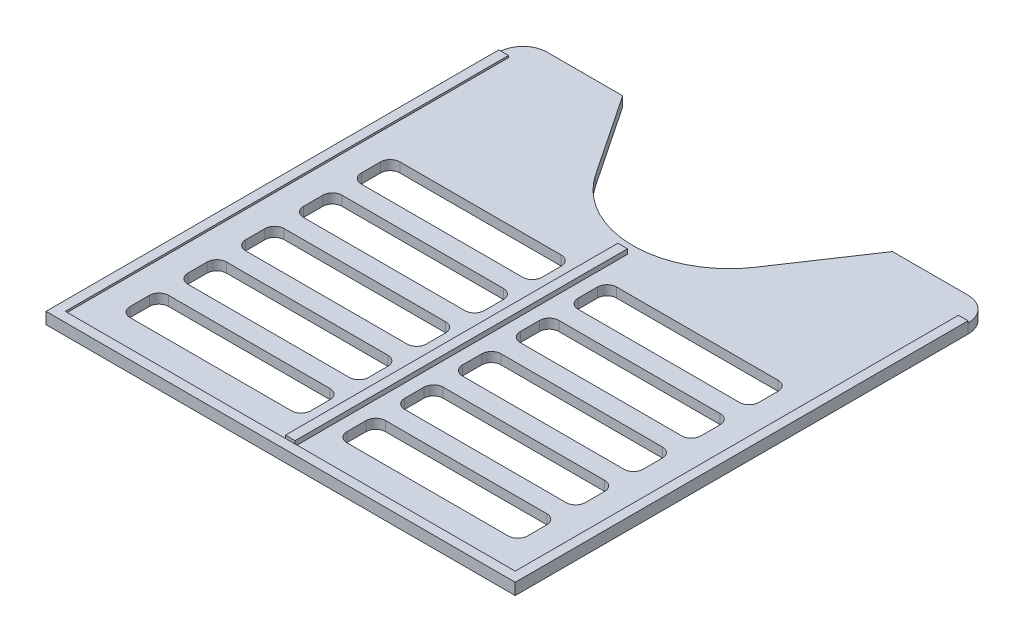
SolidWorks part; units mm, degrees
material "PVC hart"
ref_plane "Ebene vorne" through (0, 0, 0) normal (0, 0, 1) x (1, 0, 0)
ref_plane "Ebene oben" through (0, 0, 0) normal (0, 1, 0) x (1, 0, 0)
ref_plane "Ebene rechts" through (0, 0, 0) normal (1, 0, 0) x (0, 0, -1)
sketch "Skizze2" plane through (0, 0, 0) normal (0, 1, 0) x (1, 0, 0)
  line L0 (0, 82.3632) -> (0, -81.2206) construction
  line L6 (-43.7, 50) -> (-28, 50)
  line L7 (-28, 50) -> (-16.6199, 33)
  line L8 (28, 50) -> (16.6199, 33)
  line L9 (43.7, 50) -> (28, 50)
  line L10 (-48.7, -49) -> (-48.7, 45)
  line L11 (48.7, -49) -> (48.7, 45)
  line L12 (-48.7, -49) -> (48.7, -49)
  arc A0 (-16.6199, 33) -> (16.6199, 33) centre (0, 44.1257) ccw
  arc A1 (48.7, 45) -> (43.7, 50) centre (43.7, 45) ccw
  arc A2 (-48.7, 45) -> (-43.7, 50) centre (-43.7, 45) cw
  point P0 (0, 0)
  point P3 (48.7, 50)
  point P16 (-48.7, 50)
  dimension "D1" = 20
  dimension "D8" = 5
  dimension "D2" = 49
  dimension "D3" = 99
  dimension "D4" = 28
  dimension "D5" = 17
  dimension "D6" = 48.7
  dimension "D7" = 48.7
extrude "Grundkörper" add sketch "Skizze2" along normal blind 2
sketch "Skizze3" plane through (0, 2, 0) normal (0, 1, 0) x (1, 0, 0)
  line L0 (0, 51.615) -> (0, -55.1924) construction
  line L1 (-28, 50) -> (-43.7, 50) construction
  line L2 (-39.25, 15) -> (-5.75, 15)
  line L3 (-41.25, 13) -> (-41.25, 9)
  line L4 (-39.25, 7) -> (-5.75, 7)
  line L5 (-3.75, 13) -> (-3.75, 9)
  line L6 (-41.25, 15) -> (-3.75, 7) construction
  line L7 (-41.25, 7) -> (-3.75, 15) construction
  line L36 (3.75, 13) -> (3.75, 9)
  line L37 (5.75, 15) -> (39.25, 15)
  line L38 (41.25, 13) -> (41.25, 9)
  line L39 (5.75, 7) -> (39.25, 7)
  line L40 (3.75, 1) -> (3.75, -3)
  line L41 (5.75, 3) -> (39.25, 3)
  line L42 (41.25, 1) -> (41.25, -3)
  line L43 (5.75, -5) -> (39.25, -5)
  line L44 (3.75, -11) -> (3.75, -15)
  line L45 (5.75, -9) -> (39.25, -9)
  line L46 (41.25, -11) -> (41.25, -15)
  line L47 (5.75, -17) -> (39.25, -17)
  line L48 (3.75, -23) -> (3.75, -27)
  line L49 (5.75, -21) -> (39.25, -21)
  line L50 (41.25, -23) -> (41.25, -27)
  line L51 (5.75, -29) -> (39.25, -29)
  line L52 (3.75, -35) -> (3.75, -39)
  line L53 (5.75, -33) -> (39.25, -33)
  line L54 (41.25, -35) -> (41.25, -39)
  line L55 (5.75, -41) -> (39.25, -41)
  line L56 (-41.25, 1) -> (-41.25, -3)
  line L57 (-39.25, 3) -> (-5.75, 3)
  line L58 (-3.75, 1) -> (-3.75, -3)
  line L59 (-39.25, -5) -> (-5.75, -5)
  line L60 (-41.25, -11) -> (-41.25, -15)
  line L61 (-39.25, -9) -> (-5.75, -9)
  line L62 (-3.75, -11) -> (-3.75, -15)
  line L63 (-39.25, -17) -> (-5.75, -17)
  line L64 (-41.25, -23) -> (-41.25, -27)
  line L65 (-39.25, -21) -> (-5.75, -21)
  line L66 (-3.75, -23) -> (-3.75, -27)
  line L67 (-39.25, -29) -> (-5.75, -29)
  line L68 (-41.25, -35) -> (-41.25, -39)
  line L69 (-39.25, -33) -> (-5.75, -33)
  line L70 (-3.75, -35) -> (-3.75, -39)
  line L71 (-39.25, -41) -> (-5.75, -41)
  arc A0 (41.25, 9) -> (39.25, 7) centre (39.25, 9) cw
  arc A1 (39.25, 15) -> (41.25, 13) centre (39.25, 13) cw
  arc A2 (3.75, 13) -> (5.75, 15) centre (5.75, 13) cw
  arc A3 (3.75, 9) -> (5.75, 7) centre (5.75, 9) ccw
  arc A4 (3.75, -3) -> (5.75, -5) centre (5.75, -3) ccw
  arc A5 (3.75, 1) -> (5.75, 3) centre (5.75, 1) cw
  arc A6 (39.25, 3) -> (41.25, 1) centre (39.25, 1) cw
  arc A7 (41.25, -3) -> (39.25, -5) centre (39.25, -3) cw
  arc A8 (39.25, -9) -> (41.25, -11) centre (39.25, -11) cw
  arc A9 (41.25, -15) -> (39.25, -17) centre (39.25, -15) cw
  arc A10 (3.75, -15) -> (5.75, -17) centre (5.75, -15) ccw
  arc A11 (3.75, -11) -> (5.75, -9) centre (5.75, -11) cw
  arc A12 (3.75, -27) -> (5.75, -29) centre (5.75, -27) ccw
  arc A13 (3.75, -23) -> (5.75, -21) centre (5.75, -23) cw
  arc A14 (39.25, -21) -> (41.25, -23) centre (39.25, -23) cw
  arc A15 (41.25, -27) -> (39.25, -29) centre (39.25, -27) cw
  arc A16 (41.25, -39) -> (39.25, -41) centre (39.25, -39) cw
  arc A17 (39.25, -33) -> (41.25, -35) centre (39.25, -35) cw
  arc A18 (3.75, -39) -> (5.75, -41) centre (5.75, -39) ccw
  arc A19 (3.75, -35) -> (5.75, -33) centre (5.75, -35) cw
  arc A20 (-5.75, -33) -> (-3.75, -35) centre (-5.75, -35) cw
  arc A21 (-3.75, -39) -> (-5.75, -41) centre (-5.75, -39) cw
  arc A22 (-41.25, -39) -> (-39.25, -41) centre (-39.25, -39) ccw
  arc A23 (-41.25, -35) -> (-39.25, -33) centre (-39.25, -35) cw
  arc A24 (-5.75, -21) -> (-3.75, -23) centre (-5.75, -23) cw
  arc A25 (-3.75, -27) -> (-5.75, -29) centre (-5.75, -27) cw
  arc A26 (-41.25, -27) -> (-39.25, -29) centre (-39.25, -27) ccw
  arc A27 (-41.25, -23) -> (-39.25, -21) centre (-39.25, -23) cw
  arc A28 (-3.75, -15) -> (-5.75, -17) centre (-5.75, -15) cw
  arc A29 (-5.75, -9) -> (-3.75, -11) centre (-5.75, -11) cw
  arc A30 (-41.25, -15) -> (-39.25, -17) centre (-39.25, -15) ccw
  arc A31 (-41.25, -11) -> (-39.25, -9) centre (-39.25, -11) cw
  arc A32 (-3.75, -3) -> (-5.75, -5) centre (-5.75, -3) cw
  arc A33 (-5.75, 3) -> (-3.75, 1) centre (-5.75, 1) cw
  arc A34 (-41.25, -3) -> (-39.25, -5) centre (-39.25, -3) ccw
  arc A35 (-41.25, 1) -> (-39.25, 3) centre (-39.25, 1) cw
  arc A36 (-5.75, 7) -> (-3.75, 9) centre (-5.75, 9) ccw
  arc A37 (-41.25, 9) -> (-39.25, 7) centre (-39.25, 9) ccw
  arc A38 (-39.25, 15) -> (-41.25, 13) centre (-39.25, 13) ccw
  arc A39 (-5.75, 15) -> (-3.75, 13) centre (-5.75, 13) cw
  point P3 (-22.5, 11)
  dimension "D7" = 2
  dimension "D1" = 37.5
  dimension "D2" = 8
  dimension "D3" = 22.5
  dimension "D4" = 35
  dimension "D5" = 2
  dimension "D6" = 5
extrude "Lüftungen" cut sketch "Skizze3" against normal up to surface (2 mm away) up to face at (0, 0, -25.1197)
sketch "Skizze4" plane through (0, 2, 0) normal (0, 1, 0) x (1, 0, 0)
  line L0 (0, 53.6109) -> (0, -55.0435) construction
  line L1 (-48.7, -49) -> (48.7, -49) construction
  line L2 (-1, 22) -> (1, 22)
  line L3 (-1, 22) -> (-1, -47)
  line L4 (-1, -47) -> (1, -47)
  line L5 (1, 22) -> (1, -47)
  dimension "D1" = 2
  dimension "D2" = 69
  dimension "D3" = 2
extrude "Strebe" add sketch "Skizze4" along normal blind 1
sketch "Skizze5" plane through (0, 2, 0) normal (0, 1, 0) x (1, 0, 0)
  line L0 (-48.7, 45) -> (-46.7, 45)
  line L1 (-46.7, 45) -> (-46.7, -47)
  line L2 (-46.7, -47) -> (46.7, -47)
  line L3 (46.7, -47) -> (46.7, 45)
  line L4 (46.7, 45) -> (48.7, 45)
  line L5 (48.7, 45) -> (48.7, -49)
  line L6 (48.7, -49) -> (-48.7, -49)
  line L7 (-48.7, -49) -> (-48.7, 45)
  line L8 (-1, -47) -> (1, -47) construction
  dimension "D1" = 2
  dimension "D2" = 2
extrude "Strebe außen" add sketch "Skizze5" along normal blind 0.4
